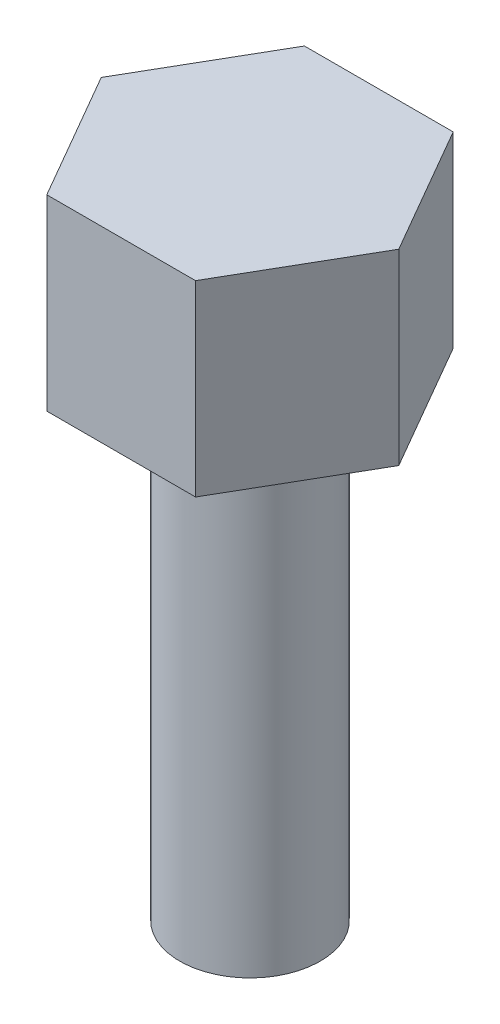
SolidWorks part; units mm, degrees
ref_plane "Front Plane" through (0, 0, 0) normal (0, 0, 1) x (1, 0, 0)
ref_plane "Top Plane" through (0, 0, 0) normal (0, 1, 0) x (1, 0, 0)
ref_plane "Right Plane" through (0, 0, 0) normal (1, 0, 0) x (0, 0, -1)
sketch "Sketch1" plane through (0, 0, 0) normal (0, 1, 0) x (1, 0, 0)
  line L1 (3.1754, 0) -> (1.5877, 2.75)
  line L2 (1.5877, 2.75) -> (-1.5877, 2.75)
  line L3 (-1.5877, 2.75) -> (-3.1754, 0)
  line L4 (-3.1754, 0) -> (-1.5877, -2.75)
  line L5 (-1.5877, -2.75) -> (1.5877, -2.75)
  line L6 (1.5877, -2.75) -> (3.1754, 0)
  circle A0 centre (0, 0) radius 2.75 construction
  circle A1 centre (0, 0) radius 1.5
  dimension "D1" = 3
  dimension "D2" = 5.5
extrude "Boss-Extrude1" add sketch "Sketch1" along normal blind 4 contours L3 L4 L5 L6 L1 L2
sketch "Sketch2" plane through (0, 0, 0) normal (0, -1, 0) x (1, 0, 0)
  circle A0 centre (0, 0) radius 1.5
  dimension "D1" = 3
extrude "Boss-Extrude2" add sketch "Sketch2" along normal blind 10
